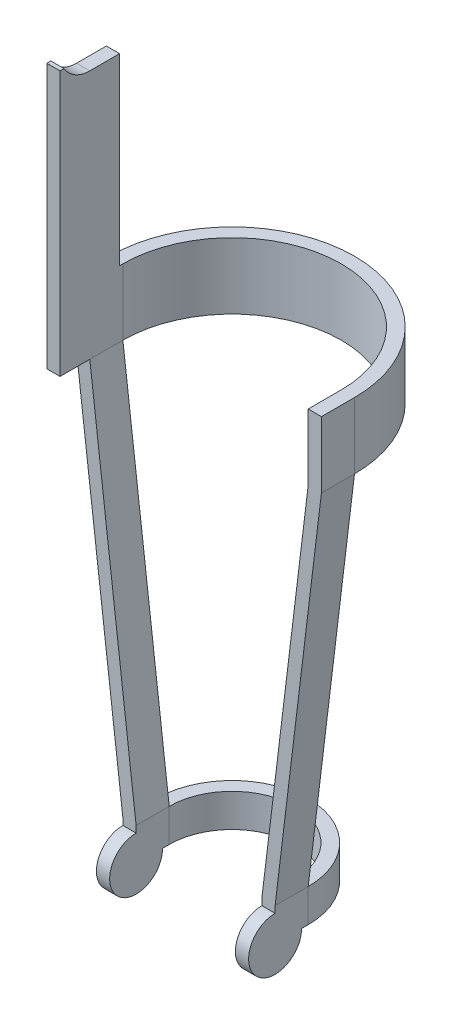
SolidWorks part; units mm, degrees
ref_plane "Front" through (0, 0, 0) normal (0, 0, 1) x (1, 0, 0)
ref_plane "Top" through (0, 0, 0) normal (0, 1, 0) x (1, 0, 0)
ref_plane "Right" through (0, 0, 0) normal (1, 0, 0) x (0, 0, -1)
sketch "草图1" plane through (0, 0, 0) normal (1, 0, 0) x (0, 0, -1)
  line L0 (-38, 0) -> (38, 0)
  line L1 (0, 0) -> (0, 113.6099) construction
  line L2 (0, 0) -> (0, 316)
  line L3 (-66, 270) -> (66, 270)
  line L4 (-15, 316) -> (15, 316)
  dimension "D1" = 38
  dimension "D2" = 76
  dimension "D3" = 132
  dimension "D4" = 66
  dimension "D5" = 270
  dimension "D6" = 30
  dimension "D7" = 15
sketch "草图2" plane through (0, 0, 0) normal (0, 1, 0) x (1, 0, 0)
  line L0 (-46, 0) -> (46, 0) construction
  line L1 (0, 46) -> (0, -46) construction
  line L4 (-46, 0) -> (-46, -20)
  line L5 (-46, -20) -> (-38, -20)
  line L6 (-38, 0) -> (-38, -20)
  line L8 (46, 0) -> (46, -20)
  line L9 (46, -20) -> (38, -20)
  line L10 (38, 0) -> (38, -20)
  arc A0 (38, 0) -> (-38, 0) centre (0, 0) ccw
  arc A1 (46, 0) -> (-46, 0) centre (0, 0) ccw
  dimension "D4" = 20
  dimension "D6" = 20
  dimension "D7" = 8
extrude "凸台-拉伸1" add sketch "草图2" along normal blind 20
sketch "草图3" plane through (-46, 0, 0) normal (-1, 0, 0) x (0, 0, 1)
  circle A0 centre (20, 0) radius 16
extrude "凸台-拉伸2" add sketch "草图3" against normal blind 8
sketch "草图4" plane through (46, 0, 0) normal (1, 0, 0) x (0, 0, -1)
  circle A0 centre (-20, 0) radius 16
extrude "凸台-拉伸3" add sketch "草图4" against normal blind 8
sketch3d "3D草图1"
  line L0 (0, 270, 66) -> (0, 270, -66) construction
  line L1 (0, 0, 0) -> (0, 316, 0) construction
  line L2 (0, 270, 74) -> (0, 270, -74) construction
  line L4 (-74, 270, 0) -> (-74, 270, 20)
  line L5 (-74, 270, 20) -> (-66, 270, 20)
  line L6 (-66, 270, 0) -> (-66, 270, 20)
  line L8 (74, 270, 0) -> (74, 270, 20)
  line L9 (74, 270, 20) -> (66, 270, 20)
  line L10 (66, 270, 0) -> (66, 270, 20)
  arc A0 (-66, 270, 0) -> (66, 270, 0) centre (0, 270, 0) ccw
  arc A1 (-74, 270, 0) -> (74, 270, 0) centre (0, 270, 0) ccw
  point P6 (0, 204, 0)
  point P9 (0, 196, 0)
  dimension "D1" = 20
  dimension "D2" = 8
  dimension "D3" = 20
  dimension "D4" = 8
extrude "凸台-拉伸4" add sketch "3D草图1" along direction (0, 1, 0) on the side of the normal mid plane 40 separate body
sketch "草图5" plane through (0, 20, 0) normal (0, 1, 0) x (1, 0, 0)
  line L1 (46, -20) -> (38, -20)
  line L2 (46, -20) -> (46, 0)
  line L3 (46, 0) -> (38, 0)
  line L4 (38, -20) -> (38, 0)
sketch "草图6" plane through (0, 0, 20) normal (0, 0, 1) x (1, 0, 0)
  line L0 (46, 20) -> (74, 250)
sweep "扫描1" add profiles "草图5" path "草图6"
sketch "草图7" plane through (0, 20, 0) normal (0, 1, 0) x (1, 0, 0)
  line L1 (-46, -20) -> (-38, -20)
  line L2 (-46, -20) -> (-46, 0)
  line L3 (-46, 0) -> (-38, 0)
  line L4 (-38, -20) -> (-38, 0)
sketch "草图8" plane through (0, 0, 20) normal (0, 0, 1) x (1, 0, 0)
  line L0 (-46, 20) -> (-74, 250)
sweep "扫描2" add profiles "草图7" path "草图8"
sketch "草图10" plane through (0, 250, 0) normal (0, -1, 0) x (1, 0, 0)
  line L0 (-74, 20) -> (74, 20) construction
  line L1 (-74, 20) -> (-74, 0) construction
  line L2 (-74, 2) -> (-66, 2)
  line L3 (-74, 2) -> (-74, 38)
  line L4 (-74, 38) -> (-66, 38)
  line L5 (-66, 2) -> (-66, 38)
  dimension "D1" = 36
  dimension "D2" = 18
  dimension "D3" = 8
extrude "凸台-拉伸5" add sketch "草图10" against normal blind 160
sketch "草图12" plane through (-74, 0, 0) normal (-1, 0, 0) x (0, 0, 1)
  line L0 (20, 410) -> (20, 441.6329) construction
  line L1 (38, 410) -> (2, 410) construction
  line L2 (2, 410) -> (38, 410) construction
  line L3 (20, 401) -> (2, 401)
  line L4 (2, 410) -> (2, 290) construction
  line L5 (2, 401) -> (2, 419)
  arc A0 (20, 401) -> (2, 419) centre (20, 419) ccw
  dimension "D1" = 9
extrude "切除-拉伸3" cut sketch "草图12" against normal blind 160
